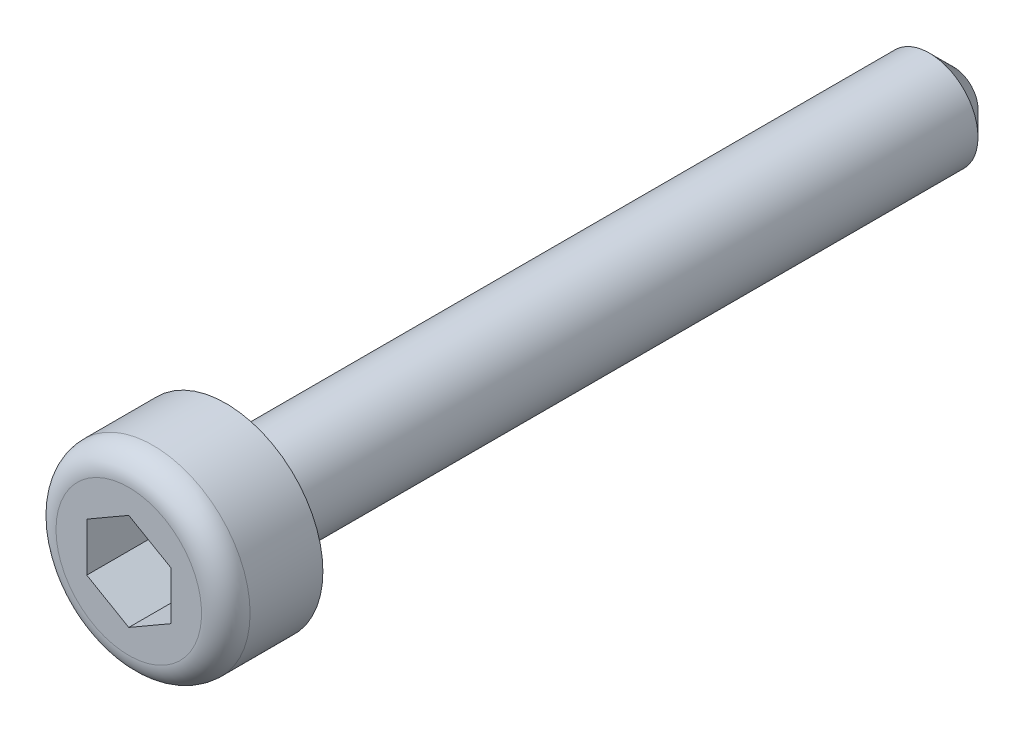
SolidWorks part; units mm, degrees
ref_plane "Front Plane" through (0, 0, 0) normal (0, 0, 1) x (1, 0, 0)
ref_plane "Top Plane" through (0, 0, 0) normal (0, 1, 0) x (1, 0, 0)
ref_plane "Right Plane" through (0, 0, 0) normal (1, 0, 0) x (0, 0, -1)
sketch "Sketch1" plane through (0, 0, 0) normal (1, 0, 0) x (0, 0, -1)
  line L0 (-156.2916, 0) -> (7658.2872, 0) construction
  line L1 (0, 0) -> (0, 4)
  line L2 (0, 4) -> (4, 4)
  line L3 (4, 4) -> (4, 2)
  line L4 (4, 2) -> (34, 2)
  line L5 (34, 2) -> (34, 0)
  line L6 (34, 0) -> (0, 0)
  dimension "D1" = 4
  dimension "D2" = 30
  dimension "D3" = 4
  dimension "D4" = 8
revolve "Body" add sketch "Sketch1" angle 360 about L0
sketch "Sketch2" plane through (0, 0, 0) normal (0, 0, 1) x (1, 0, 0)
  line L1 (0, 2) -> (-1.7321, 1)
  line L2 (-1.7321, 1) -> (-1.7321, -1)
  line L3 (-1.7321, -1) -> (0, -2)
  line L4 (0, -2) -> (1.7321, -1)
  line L5 (1.7321, -1) -> (1.7321, 1)
  line L6 (1.7321, 1) -> (0, 2)
  circle A0 centre (0, 0) radius 2 construction
  dimension "D1" = 4
extrude "Footprint" cut sketch "Sketch2" against normal blind 3
chamfer "Chamfer1" distance 1 angle 45 1 edges at (2, 0, -34)
fillet "Fillet1" radius 1 1 edges at (4, 0, 0)
